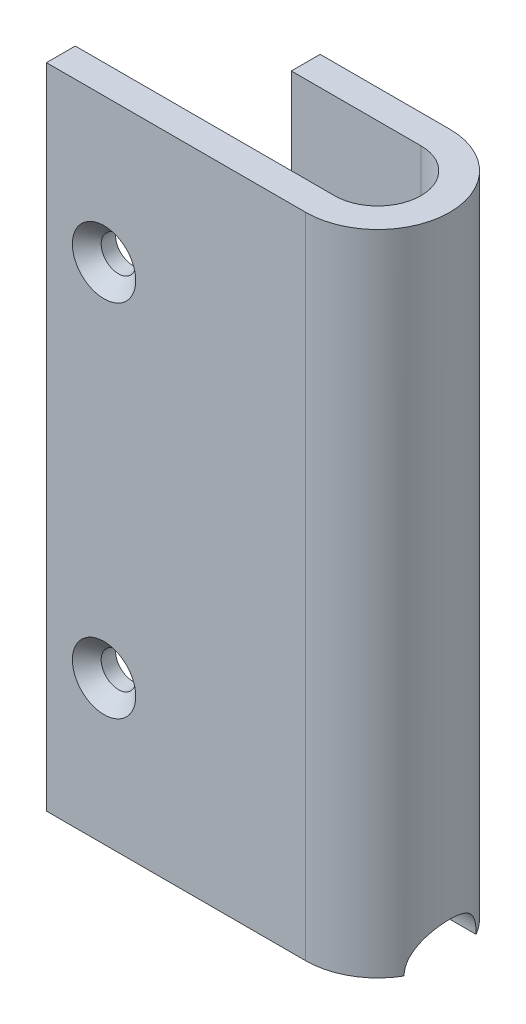
SolidWorks part; units mm, degrees
ref_plane "Front Plane" through (0, 0, 0) normal (0, 0, 1) x (1, 0, 0)
ref_plane "Top Plane" through (0, 0, 0) normal (0, 1, 0) x (1, 0, 0)
ref_plane "Right Plane" through (0, 0, 0) normal (1, 0, 0) x (0, 0, -1)
sketch "Sketch1" plane through (0, 0, 0) normal (0, 1, 0) x (1, 0, 0)
  line L0 (0, 3) -> (-9, 3)
  line L1 (0, -3) -> (-18, -3)
  line L2 (0, -5) -> (-18, -5)
  line L3 (0, 5) -> (-9, 5)
  line L4 (-9, 5) -> (-9, 3)
  line L5 (-18, -3) -> (-18, -5)
  arc A0 (0, -3) -> (0, 3) centre (0, 0) ccw
  arc A1 (0, -5) -> (0, 5) centre (0, 0) ccw
  dimension "D1" = 6
  dimension "D2" = 18
  dimension "D3" = 9
  dimension "D4" = 2
extrude "Boss-Extrude1" add sketch "Sketch1" along normal blind 45
sketch "Sketch2" plane through (0, 0, -5) normal (0, 0, -1) x (-1, 0, 0)
  line L0 (9, 45) -> (9, 0) construction
  line L1 (0, 0) -> (9, 0) construction
  circle A0 centre (9, 17.5) radius 1
  dimension "D1" = 2
  dimension "D2" = 17.5
extrude "Cut-Extrude1" cut sketch "Sketch2" against normal blind 5
sketch "Sketch3" plane through (0, 0, 0) normal (1, 0, 0) x (0, 0, -1)
  circle A0 centre (0, 0) radius 2.5
  dimension "D1" = 5
extrude "Cut-Extrude2" cut sketch "Sketch3" along normal blind 6
sketch "Sketch4" plane through (0, 0, 5) normal (0, 0, 1) x (1, 0, 0)
  line L0 (-18, 45) -> (-14, 45) construction
  line L1 (-18, 45) -> (0, 45) construction
  line L2 (-14, 45) -> (-14, 35) construction
  line L3 (-14, 35) -> (-14, 10) construction
  dimension "D1" = 4
  dimension "D2" = 10
  dimension "D3" = 25
hole_wizard "CSK for M2 Countersunk Flat Head Screw1" positions "3DSketch1" profile "Sketch5" countersink size "M2" standard "DIN" end condition through all
sketch3d "3DSketch1"
  point P0 (-14, 35, 5)
  point P3 (-14, 10, 5)
sketch "Sketch5" plane through (-14, 35, 5) normal (1, 0, 0) x (0, -1, 0)
  line L0 (0, 0) -> (0, 10)
  line L1 (0, 10) -> (1.2, 10)
  line L2 (1.2, 10) -> (1.2, 1)
  line L3 (1.2, 1) -> (2.2, 0)
  line L5 (2.2, 0) -> (0, 0)
  line L6 (-1.2, 1) -> (-2.2, 0) construction
  line L11 (0, -6.35) -> (0, 107.95) construction
  dimension "Thru Hole Dia." = 2.4
  dimension "Thru Hole Depth" = 10
  dimension "Near C'Sink Dia." = 4.4
  dimension "Near C'Sink Angle" = 90
